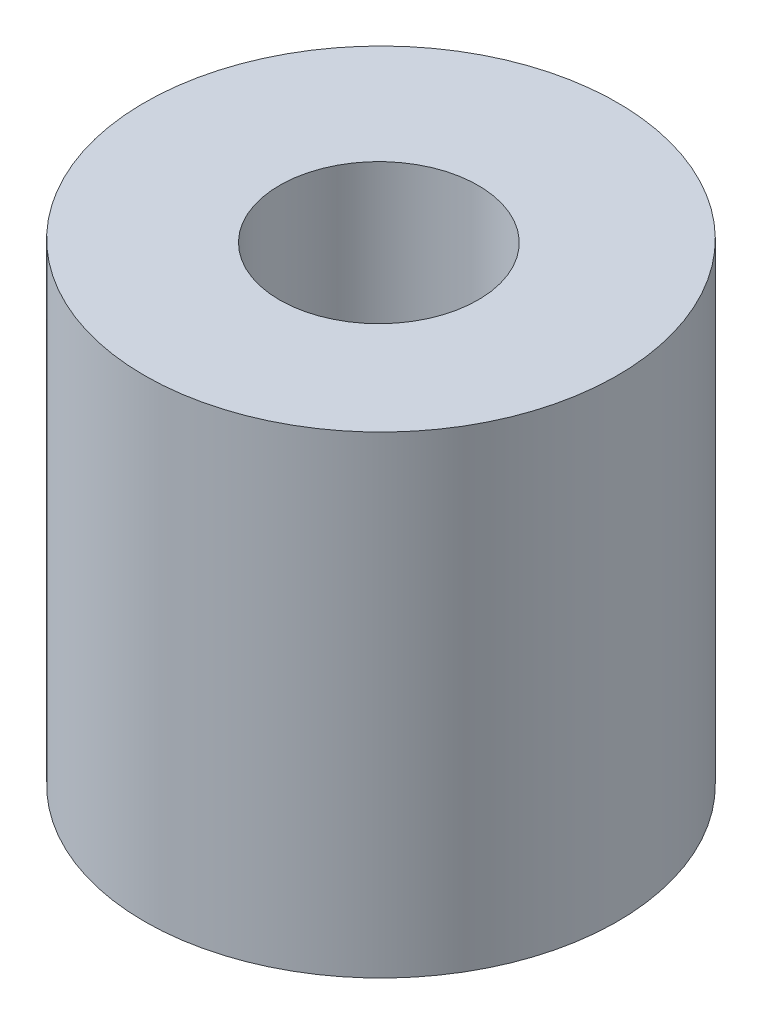
SolidWorks part; units mm, degrees
ref_plane "前视基准面" through (0, 0, 0) normal (0, 0, 1) x (1, 0, 0)
ref_plane "上视基准面" through (0, 0, 0) normal (0, 1, 0) x (1, 0, 0)
ref_plane "右视基准面" through (0, 0, 0) normal (1, 0, 0) x (0, 0, -1)
other "Configuration Table"
sketch "草图1" plane through (0, 0, 0) normal (0, 1, 0) x (1, 0, 0)
  circle A0 centre (0.0221, -0.0111) radius 1.05
  circle A1 centre (0, 0.0332) radius 2.5
  dimension "D1" = 2.1
  dimension "D2" = 5
extrude "凸台-拉伸1" add sketch "草图1" along normal blind 5
